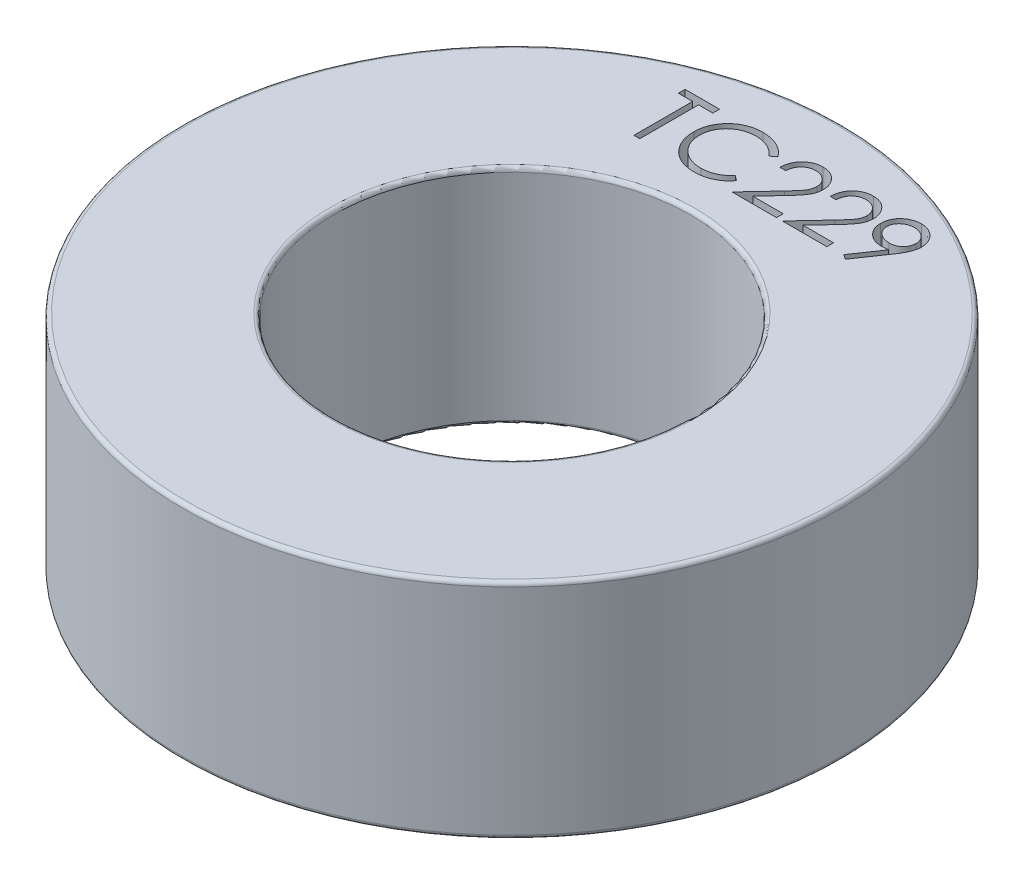
SolidWorks part; units mm, degrees
ref_plane "Front Plane" through (0, 0, 0) normal (0, 0, 1) x (1, 0, 0)
ref_plane "Top Plane" through (0, 0, 0) normal (0, 1, 0) x (1, 0, 0)
ref_plane "Right Plane" through (0, 0, 0) normal (1, 0, 0) x (0, 0, -1)
sketch "Toroidal Core TC229" plane through (0, 0, 0) normal (0, 0, 1) x (1, 0, 0)
  line L0 (0, -8.108) -> (0, 13.3131) construction
  line L2 (6.6461, 0) -> (11.8539, 0)
  line L3 (6.5, 0.1461) -> (6.5, 7.9739)
  line L4 (6.6461, 8.12) -> (11.8539, 8.12)
  line L5 (12, 0.1461) -> (12, 7.9739)
  arc A0 (6.6461, 0) -> (6.5, 0.1461) centre (6.6461, 0.1461) cw
  arc A1 (11.8539, 0) -> (12, 0.1461) centre (11.8539, 0.1461) ccw
  arc A2 (11.8539, 8.12) -> (12, 7.9739) centre (11.8539, 7.9739) cw
  arc A3 (6.5, 7.9739) -> (6.6461, 8.12) centre (6.6461, 7.9739) cw
  point P9 (6.5, 0)
  point P12 (12, 0)
  point P15 (12, 8.12)
  point P18 (6.5, 8.12)
  dimension "D4" = 0.1461
  dimension "D1" = 5.5
  dimension "D2" = 8.12
  dimension "D3" = 6.5
revolve "Revolve2" add sketch "Toroidal Core TC229" angle 360 about L0
sketch "Sketch1" plane through (0, 8.12, 0) normal (0, 1, 0) x (1, 0, 0)
  text T0 "TC229" font "Century Gothic" height in points 9
extrude "Cut-Extrude1" cut sketch "Sketch1" against normal blind 1
